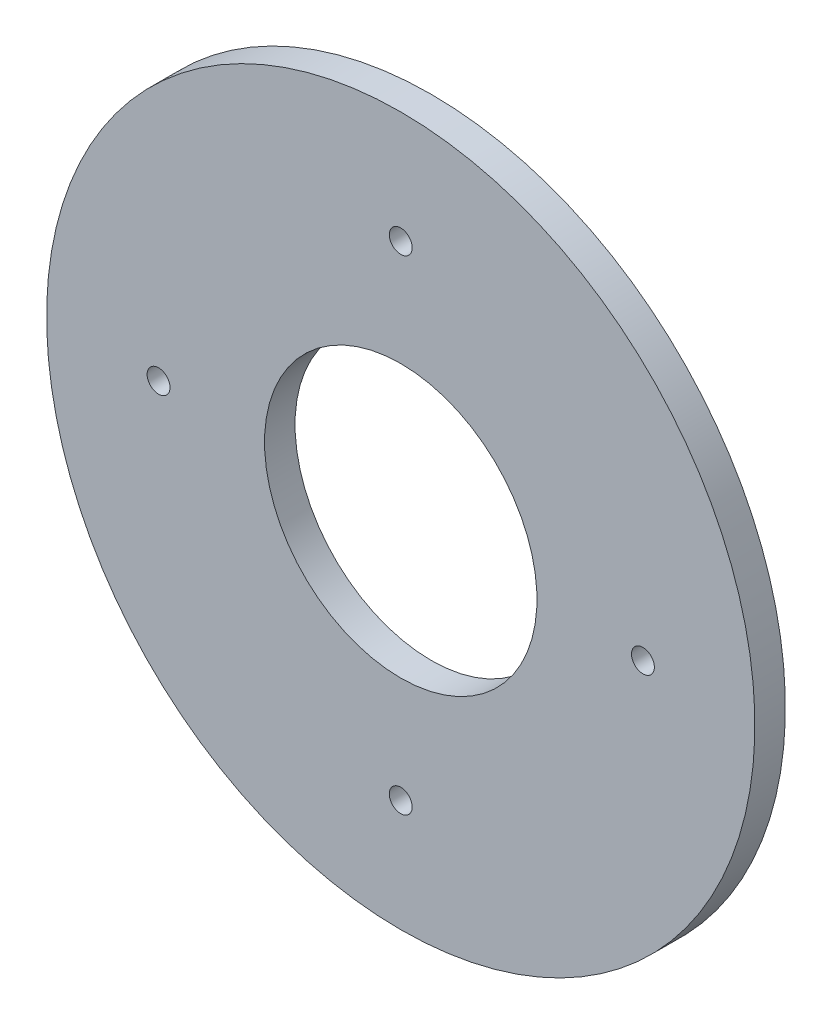
SolidWorks part; units mm, degrees
material "ﾎﾟﾘｴﾁﾚﾝｲﾐﾝ(PEI)"
ref_plane "正面" through (0, 0, 0) normal (0, 0, 1) x (1, 0, 0)
ref_plane "平面" through (0, 0, 0) normal (0, 1, 0) x (1, 0, 0)
ref_plane "右側面" through (0, 0, 0) normal (1, 0, 0) x (0, 0, -1)
sketch "ｽｹｯﾁ1" plane through (0, 0, 0) normal (1, 0, 0) x (0, 0, -1)
  line L0 (-5.6, 0) -> (-15.6, 0)
  line L1 (0, 0) -> (-5.6, 0)
  line L2 (0, 0) -> (0, 65)
  line L3 (0, 65) -> (-5.6, 65)
  line L4 (-5.6, 0) -> (-5.6, 65)
  arc A0 (-15.6, 0) -> (-5.6, 65) centre (484.4, -43.6538) cw
  dimension "D1" = 65
  dimension "D2" = 5.6
  dimension "D3" = 10
  dimension "D4" = 500
revolve "回転1" add sketch "ｽｹｯﾁ1" angle 360 about L1
sketch "ｽｹｯﾁ2" plane through (0, 0, 0) normal (0, 0, -1) x (-1, 0, 0)
  circle A0 centre (0, 0) radius 25
  dimension "D1" = 50
extrude "ｶｯﾄ - 押し出し1" cut sketch "ｽｹｯﾁ2" against normal through all
sketch "ｽｹｯﾁ3" plane through (0, 0, 0) normal (0, 0, -1) x (-1, 0, 0)
  circle A0 centre (0, 0) radius 44.45 construction
  circle A1 centre (0, 44.45) radius 2.1
  circle A2 centre (44.45, 0) radius 2.1
  circle A3 centre (0, -44.45) radius 2.1
  circle A4 centre (-44.45, 0) radius 2.1
  dimension "D1" = 88.9
  dimension "D2" = 4.2
  dimension "D3" = 4
extrude "ｶｯﾄ - 押し出し2" cut sketch "ｽｹｯﾁ3" against normal through all
